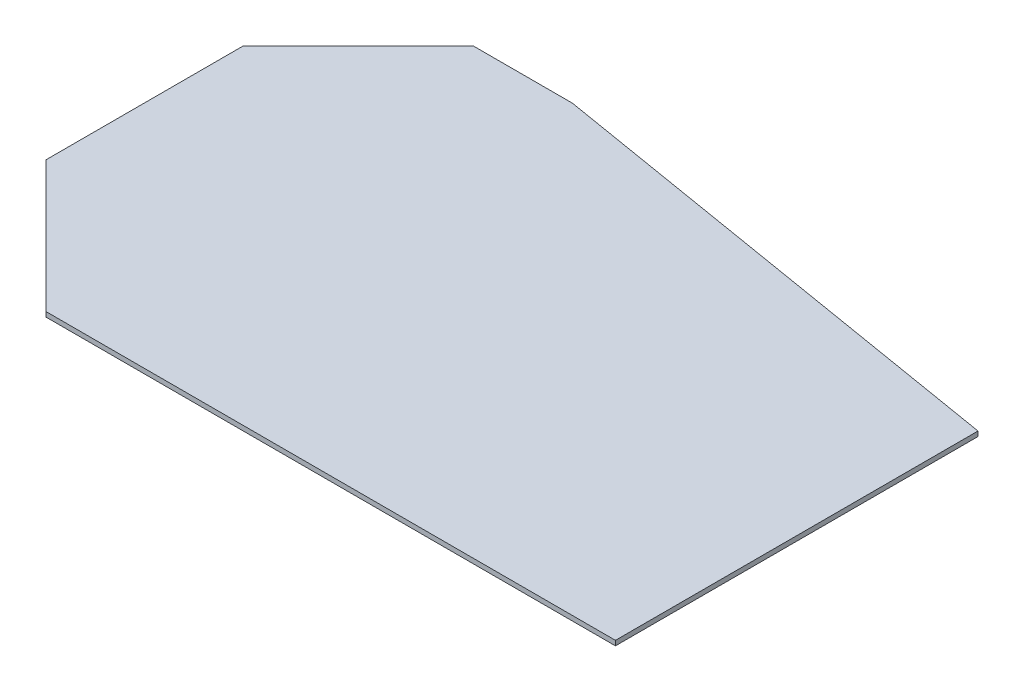
SolidWorks part; units mm, degrees
ref_plane "Plan de face" through (0, 0, 0) normal (0, 0, 1) x (1, 0, 0)
ref_plane "Plan de dessus" through (0, 0, 0) normal (0, 1, 0) x (1, 0, 0)
ref_plane "Plan de droite" through (0, 0, 0) normal (1, 0, 0) x (0, 0, -1)
sketch "Esquisse1" plane through (0, 0, 0) normal (0, 1, 0) x (1, 0, 0)
  line L0 (115, 10) -> (465, 10)
  line L1 (165.2483, 283) -> (468, 232.5414)
  line L2 (0, 0) -> (0, 300)
  line L3 (0, 300) -> (500, 300)
  line L4 (500, 0) -> (500, 300)
  line L5 (468, 232.5414) -> (468, 7)
  line L6 (0, 0) -> (0, 10)
  line L7 (465, 230) -> (465, 10)
  line L8 (500, 0) -> (500, 10)
  line L9 (0, 300) -> (500, 300)
  line L10 (0, 300) -> (0, 290)
  line L11 (0, 290) -> (35, 290)
  line L12 (500, 300) -> (500, 290)
  line L13 (0, 300) -> (35, 300)
  line L14 (0, 300) -> (0, 0)
  line L15 (113.7574, 7) -> (468, 7)
  line L16 (35, 300) -> (35, 290)
  line L17 (500, 300) -> (465, 300)
  line L18 (500, 300) -> (500, 0)
  line L19 (113.7574, 7) -> (32, 88.7574)
  line L20 (32, 211.2426) -> (32, 88.7574)
  line L21 (103.7574, 283) -> (32, 211.2426)
  line L22 (103.7574, 283) -> (165.2483, 283)
  line L24 (115, 10) -> (35, 90)
  line L26 (35, 210) -> (35, 90)
  line L27 (105, 280) -> (35, 210)
  line L34 (105, 280) -> (165, 280)
  line L35 (165, 280) -> (465, 230)
  point P13 (465, 10)
  dimension "D1" = 500
  dimension "D2" = 300
  dimension "D3" = 3
  dimension "D4" = 10
  dimension "D5" = 35
  dimension "D7" = 60
  dimension "D8" = 120
  dimension "D9" = 350
  dimension "D10" = 220
extrude "Boss.-Extru.1" add sketch "Esquisse1" along normal blind 3 contours L35 L34 L27 L26 L24 L0 L7 | L22 L21 L20 L19 L15 L5 L1 L34 L35 L7 L0 L24 L26 L27
